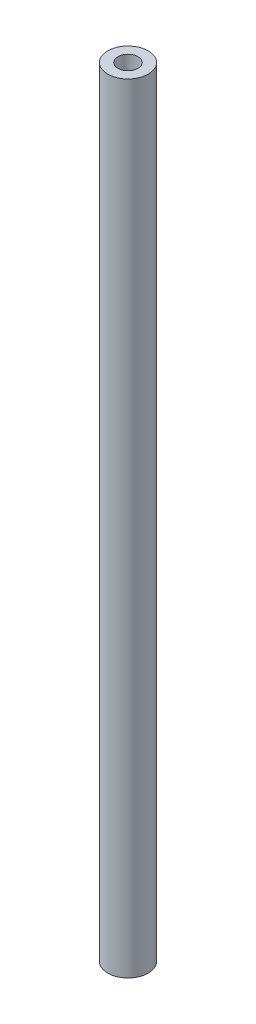
SolidWorks part; units mm, degrees
ref_plane "Front Plane" through (0, 0, 0) normal (0, 0, 1) x (1, 0, 0)
ref_plane "Top Plane" through (0, 0, 0) normal (0, 1, 0) x (1, 0, 0)
ref_plane "Right Plane" through (0, 0, 0) normal (1, 0, 0) x (0, 0, -1)
sketch "Sketch1" plane through (0, 0, 0) normal (0, 1, 0) x (1, 0, 0)
  circle A0 centre (0, 0) radius 4.7625
  circle A1 centre (0, 0) radius 9.525
  dimension "D1" = 19.05
  dimension "D2" = 9.525
extrude "Boss-Extrude1" add sketch "Sketch1" along normal blind 367.03
